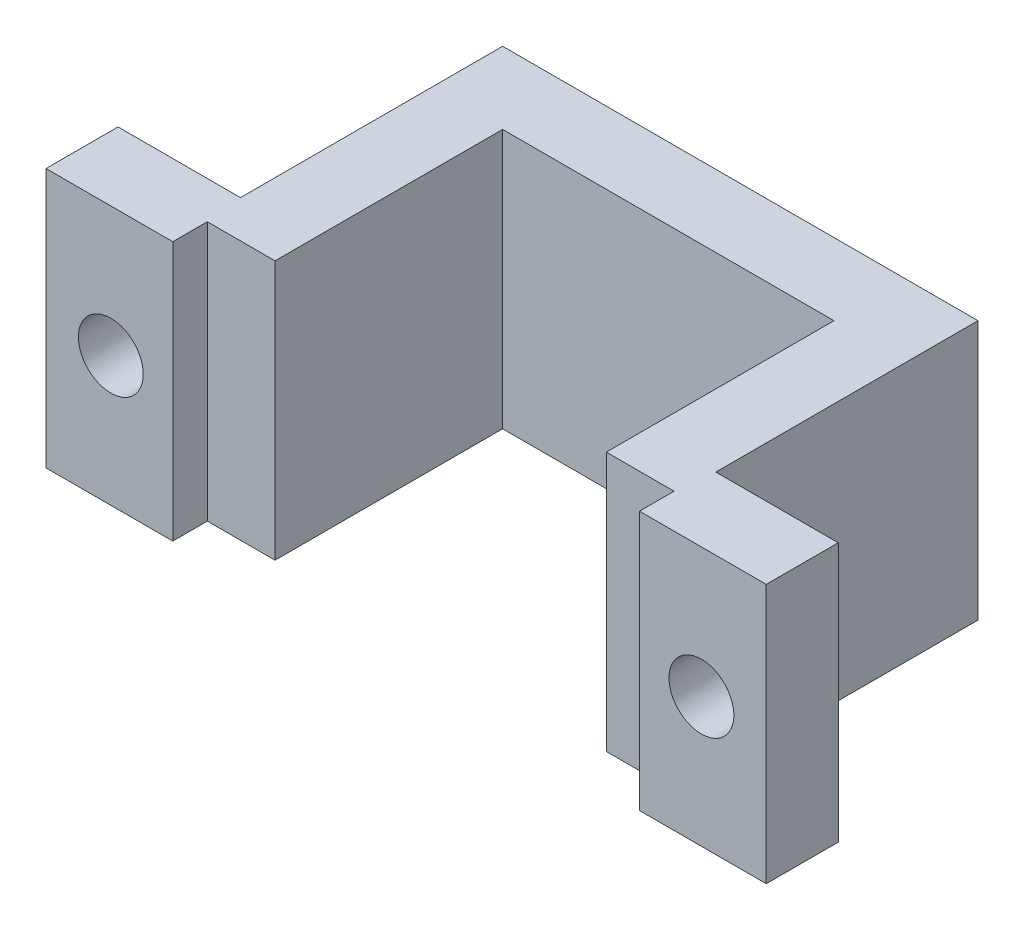
SolidWorks part; units mm, degrees
ref_plane "Front Plane" through (0, 0, 0) normal (0, 0, 1) x (1, 0, 0)
ref_plane "Top Plane" through (0, 0, 0) normal (0, 1, 0) x (1, 0, 0)
ref_plane "Right Plane" through (0, 0, 0) normal (1, 0, 0) x (0, 0, -1)
sketch "Sketch1" plane through (0, 0, 0) normal (0, 1, 0) x (1, 0, 0)
  line L0 (0, 0) -> (8.8, 0)
  line L1 (8.8, 0) -> (8.8, 2.4)
  line L2 (8.8, 2.4) -> (13.5, 2.4)
  line L3 (13.5, 2.4) -> (13.5, 18.2)
  line L4 (13.5, 18.2) -> (36.5, 18.2)
  line L5 (0, 0) -> (0, 5)
  line L6 (25, 31.9636) -> (25, 4.4364) construction
  line L7 (0, 5) -> (8.5, 5)
  line L8 (8.5, 5) -> (8.5, 23.2)
  line L9 (8.5, 23.2) -> (41.5, 23.2)
  line L10 (41.5, 5) -> (41.5, 23.2)
  line L11 (50, 5) -> (41.5, 5)
  line L12 (50, 0) -> (50, 5)
  line L13 (36.5, 2.4) -> (36.5, 18.2)
  line L14 (41.2, 2.4) -> (36.5, 2.4)
  line L15 (41.2, 0) -> (41.2, 2.4)
  line L16 (50, 0) -> (41.2, 0)
  point P11 (25, 18.2)
  point P15 (25, 23.2)
  point P19 (25, 18.2)
  dimension "D1" = 8.8
  dimension "D2" = 2.4
  dimension "D3" = 4.7
  dimension "D4" = 15.8
  dimension "D5" = 11.5
  dimension "D6" = 5
  dimension "D7" = 5
  dimension "D8" = 5
extrude "Boss-Extrude1" add sketch "Sketch1" along normal blind 18
sketch "Sketch2" plane through (0, 0, -5) normal (0, 0, -1) x (-1, 0, 0)
  line L0 (-50, 0) -> (-50, 18) construction
  line L1 (-50, 18) -> (-25, 0) construction
  line L2 (-41.5, 0) -> (-8.5, 0) construction
  line L3 (-25, 0) -> (-25, 18) construction
  line L4 (-41.5, 18) -> (-8.5, 18) construction
  line L5 (-25, 18) -> (0, 18) construction
  line L6 (0, 18) -> (0, 0) construction
  line L7 (-50, 9) -> (-45.5, 9) construction
  circle A0 centre (-45.5, 9) radius 2.25
  circle A1 centre (-4.5, 9) radius 2.25
  dimension "D1" = 4.5
  dimension "D2" = 4.5
extrude "Cut-Extrude1" cut sketch "Sketch2" against normal through all
